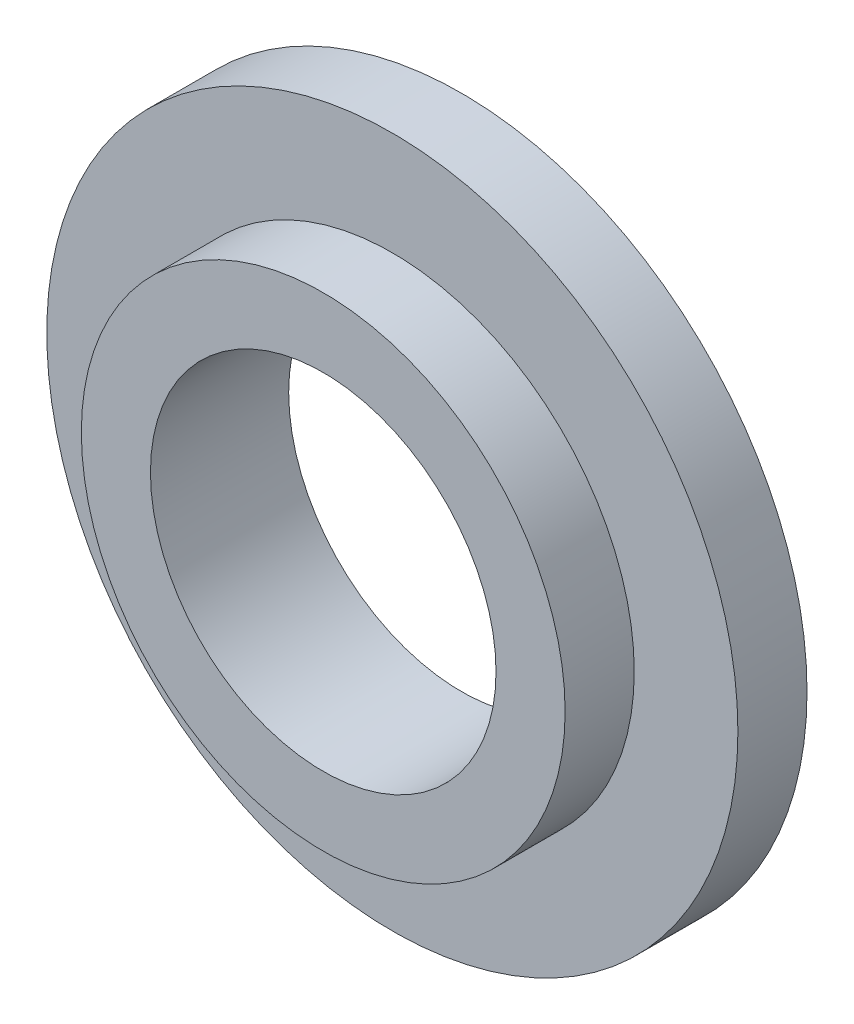
SolidWorks part; units mm, degrees
ref_plane "前视基准面" through (0, 0, 0) normal (0, 0, 1) x (1, 0, 0)
ref_plane "上视基准面" through (0, 0, 0) normal (0, 1, 0) x (1, 0, 0)
ref_plane "右视基准面" through (0, 0, 0) normal (1, 0, 0) x (0, 0, -1)
sketch "草图1" plane through (0, 0, 0) normal (0, 0, 1) x (1, 0, 0)
  circle A1 centre (0, 0) radius 5
  dimension "D2" = 10
extrude "凸台-拉伸1" add sketch "草图1" along normal blind 1
sketch "草图2" plane through (0, 0, 1) normal (0, 0, 1) x (1, 0, 0)
  circle A0 centre (0, 0) radius 3.5
  circle A1 centre (0, 0) radius 2.5
  dimension "D1" = 7
  dimension "D2" = 5
extrude "凸台-拉伸2" add sketch "草图2" along normal blind 1
sketch "草图3" plane through (0, 0, 1) normal (0, 0, 1) x (1, 0, 0)
  circle A0 centre (0, 0) radius 2.5
  dimension "D1" = 5
extrude "切除-拉伸1" cut sketch "草图3" against normal blind 5
